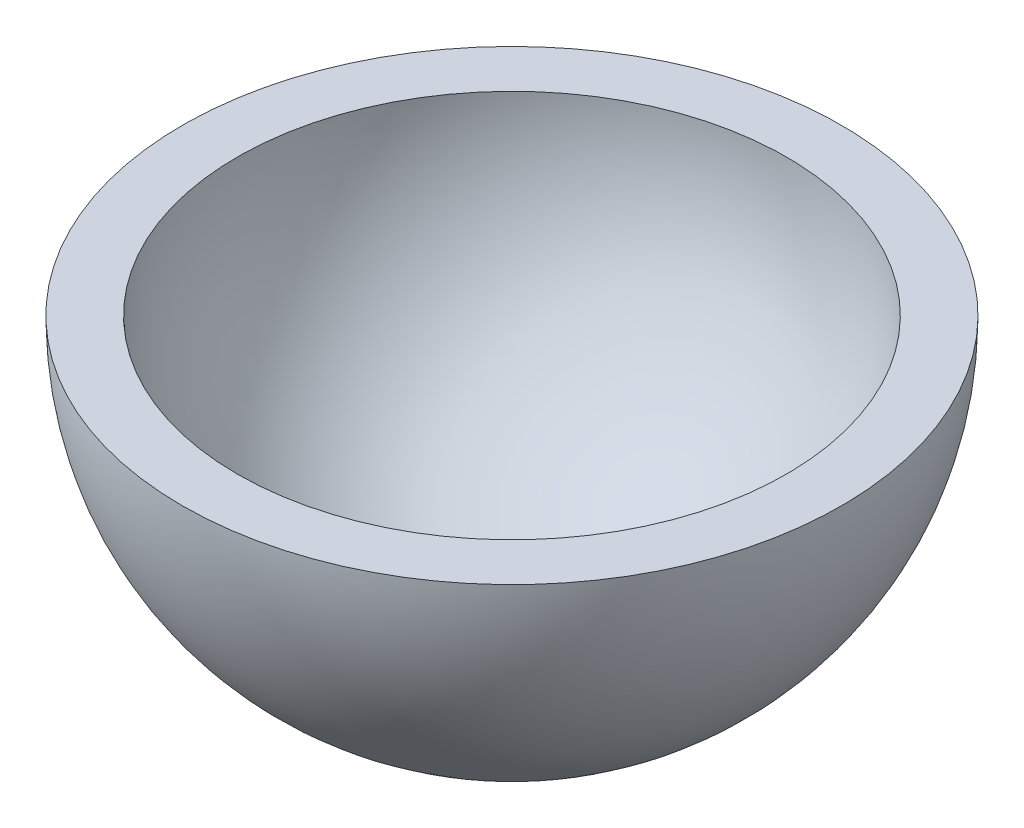
SolidWorks part; units mm, degrees
ref_plane "Front Plane" through (0, 0, 0) normal (0, 0, 1) x (1, 0, 0)
ref_plane "Top Plane" through (0, 0, 0) normal (0, 1, 0) x (1, 0, 0)
ref_plane "Right Plane" through (0, 0, 0) normal (1, 0, 0) x (0, 0, -1)
sketch "Sketch1" plane through (0, 0, 0) normal (0, 1, 0) x (1, 0, 0)
  line L0 (0, 6) -> (0, -6) construction
  line L1 (0, 6) -> (0, 5)
  line L2 (0, -5) -> (0, -6)
  arc A0 (0, 6) -> (0, -6) centre (0, 0) ccw
  arc A1 (0, 5) -> (0, -5) centre (0, 0) ccw
  dimension "D1" = 12
  dimension "D2" = 10
revolve "Revolve1" add sketch "Sketch1" angle 180 about L0
